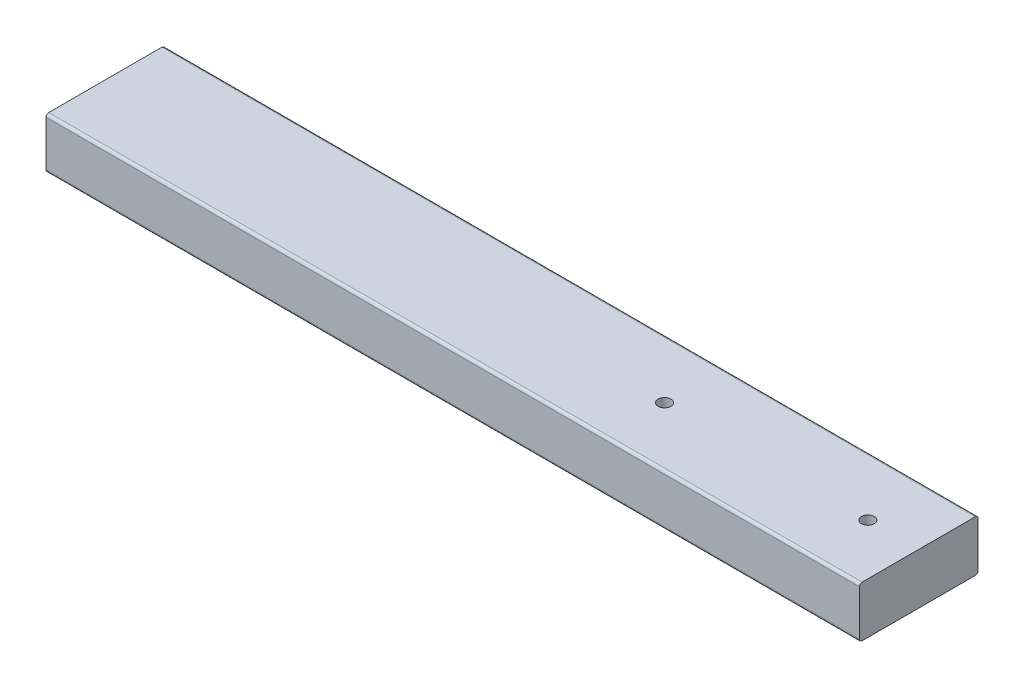
SolidWorks part; units mm, degrees
ref_plane "Front Plane" through (0, 0, 0) normal (0, 0, 1) x (1, 0, 0)
ref_plane "Top Plane" through (0, 0, 0) normal (0, 1, 0) x (1, 0, 0)
ref_plane "Right Plane" through (0, 0, 0) normal (1, 0, 0) x (0, 0, -1)
sketch "Sketch1" plane through (0, 609.6, 0) normal (1, 0, 0) x (0, 0, -1)
  line L1 (-44.45, -628.65) -> (44.45, -628.65)
  line L2 (-44.45, -628.65) -> (-44.45, -590.55)
  line L3 (-44.45, -590.55) -> (44.45, -590.55)
  line L4 (44.45, -628.65) -> (44.45, -590.55)
  line L5 (-44.45, -628.65) -> (44.45, -590.55) construction
  line L6 (-44.45, -590.55) -> (44.45, -628.65) construction
  point P0 (0, -609.6)
  dimension "D1" = 38.1
  dimension "D2" = 88.9
extrude "Boss-Extrude1" add sketch "Sketch1" along normal blind 609.6
fillet "Fillet1" radius 2 4 edges at (304.8, 19.05, 44.45) (304.8, 19.05, -44.45) (304.8, -19.05, -44.45) (304.8, -19.05, 44.45)
other "2x4<1>"
sketch "Sketch2" plane through (0, -19.05, 0) normal (0, -1, 0) x (-1, 0, 0)
  line L1 (-609.6, -42.45) -> (-609.6, 42.45) construction
  circle A0 centre (-419.1, 0) radius 4.7625
  circle A1 centre (-571.5, 0) radius 4.7625
  point P4 (0, 0)
  point P6 (-53.1338, 0)
  point P7 (-516.7779, 0)
  point P11 (-609.6, 0)
  dimension "D1" = 9.525
  dimension "D2" = 152.4
  dimension "D3" = 38.1
extrude "Cut-Extrude1" cut sketch "Sketch2" against normal through all
